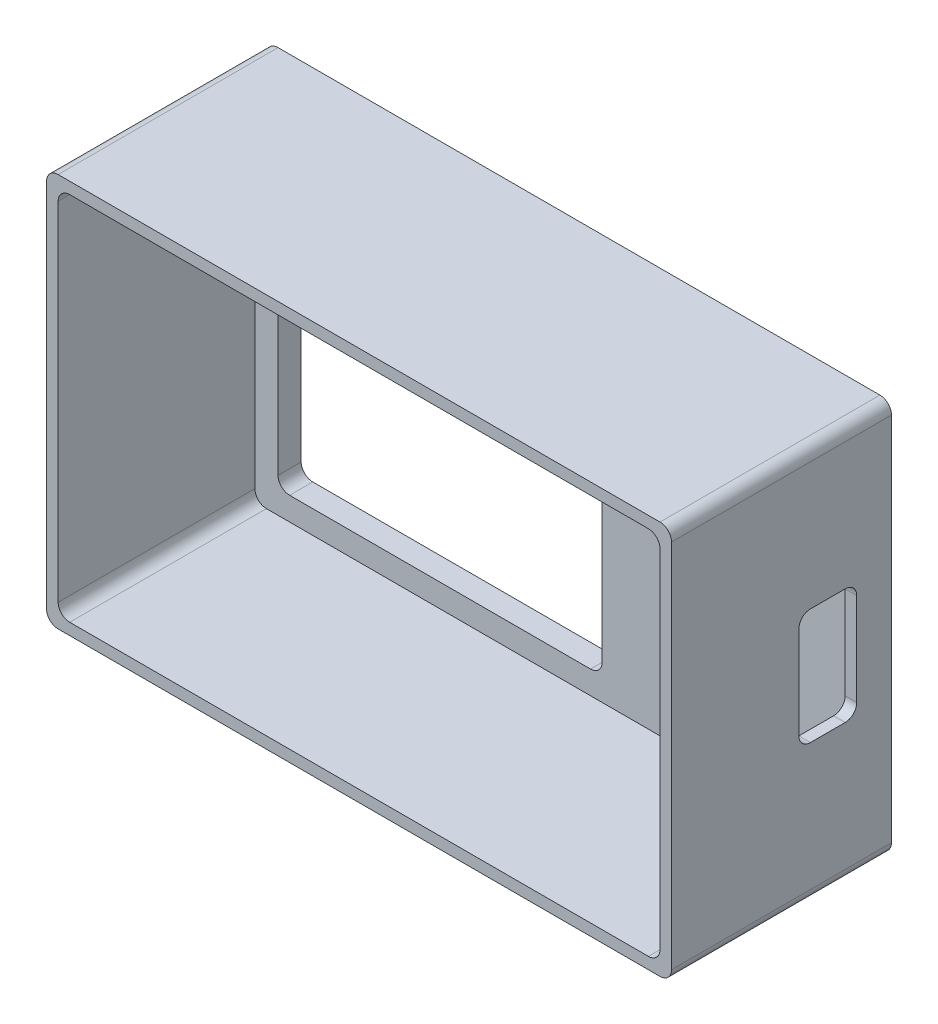
SolidWorks part; units mm, degrees
ref_plane "Front Plane" through (0, 0, 0) normal (0, 0, 1) x (1, 0, 0)
ref_plane "Top Plane" through (0, 0, 0) normal (0, 1, 0) x (1, 0, 0)
ref_plane "Right Plane" through (0, 0, 0) normal (1, 0, 0) x (0, 0, -1)
sketch "Sketch1" plane through (0, 0, 0) normal (0, 0, 1) x (1, 0, 0)
  line L1 (-26, 16) -> (26, 16) construction
  line L2 (-26, 16) -> (-26, -16) construction
  line L3 (-26, -16) -> (26, -16) construction
  line L4 (26, 16) -> (26, -16) construction
  line L5 (-26, 16) -> (26, -16) construction
  line L6 (-26, -16) -> (26, 16) construction
  line L7 (-27, 17) -> (27, 17)
  line L8 (-27, 17) -> (-27, -17)
  line L9 (-27, -17) -> (27, -17)
  line L10 (27, 17) -> (27, -17)
  line L11 (-27, 17) -> (27, -17) construction
  line L12 (-27, -17) -> (27, 17) construction
  line L13 (-24, 14) -> (4, 14)
  line L14 (-24, 14) -> (-24, -14)
  line L15 (-24, -14) -> (4, -14)
  line L16 (4, 14) -> (4, -14)
  line L17 (-24, 14) -> (4, -14) construction
  line L18 (-24, -14) -> (4, 14) construction
  point P0 (0, 0)
  point P6 (0, 0)
  point P11 (-10, 0)
  dimension "D1" = 52
  dimension "D2" = 32
  dimension "D3" = 54
  dimension "D4" = 34
  dimension "D5" = 2
  dimension "D6" = 2
  dimension "D7" = 2
  dimension "D8" = 28
extrude "Boss-Extrude1" add sketch "Sketch1" along normal blind 2
sketch "Sketch2" plane through (0, 0, 2) normal (0, 0, 1) x (1, 0, 0)
  line L1 (-27, 17) -> (27, 17)
  line L2 (-27, 17) -> (-27, -17)
  line L3 (-27, -17) -> (27, -17)
  line L4 (27, 17) -> (27, -17)
  line L5 (-27, 17) -> (27, -17) construction
  line L6 (-27, -17) -> (27, 17) construction
  line L7 (-26, 16) -> (26, 16)
  line L8 (-26, 16) -> (-26, -16)
  line L9 (-26, -16) -> (26, -16)
  line L10 (26, 16) -> (26, -16)
  line L11 (-26, 16) -> (26, -16) construction
  line L12 (-26, -16) -> (26, 16) construction
  point P0 (0, 0)
  point P7 (0, 0)
  dimension "D1" = 52
  dimension "D2" = 32
extrude "Boss-Extrude2" add sketch "Sketch2" along normal blind 17
fillet "Fillet1" radius 1 4 edges at (-26, -16, 10.5) (-26, 16, 10.5) (26, -16, 10.5) (26, 16, 10.5)
fillet "Fillet2" radius 1 4 edges at (-27, 17, 9.5) (-27, -17, 9.5) (27, -17, 9.5) (27, 17, 9.5)
sketch "Sketch3" plane through (27, 0, 0) normal (1, 0, 0) x (0, 0, -1)
  line L1 (-8, 5) -> (-3, 5)
  line L2 (-8, 5) -> (-8, -5)
  line L3 (-8, -5) -> (-3, -5)
  line L4 (-3, 5) -> (-3, -5)
  line L5 (-8, 5) -> (-3, -5) construction
  line L6 (-8, -5) -> (-3, 5) construction
  point P0 (-5.5, 0)
  dimension "D1" = 10
  dimension "D2" = 5
  dimension "D3" = 0
  dimension "D4" = 3
extrude "Cut-Extrude1" cut sketch "Sketch3" against normal blind 17
fillet "Fillet3" radius 1 4 edges at (26.5, 5, 3) (26.5, 5, 8) (26.5, -5, 8) (26.5, -5, 3)
fillet "Fillet4" radius 1 4 edges at (4, -14, 1) (4, 14, 1) (-24, -14, 1) (-24, 14, 1)
